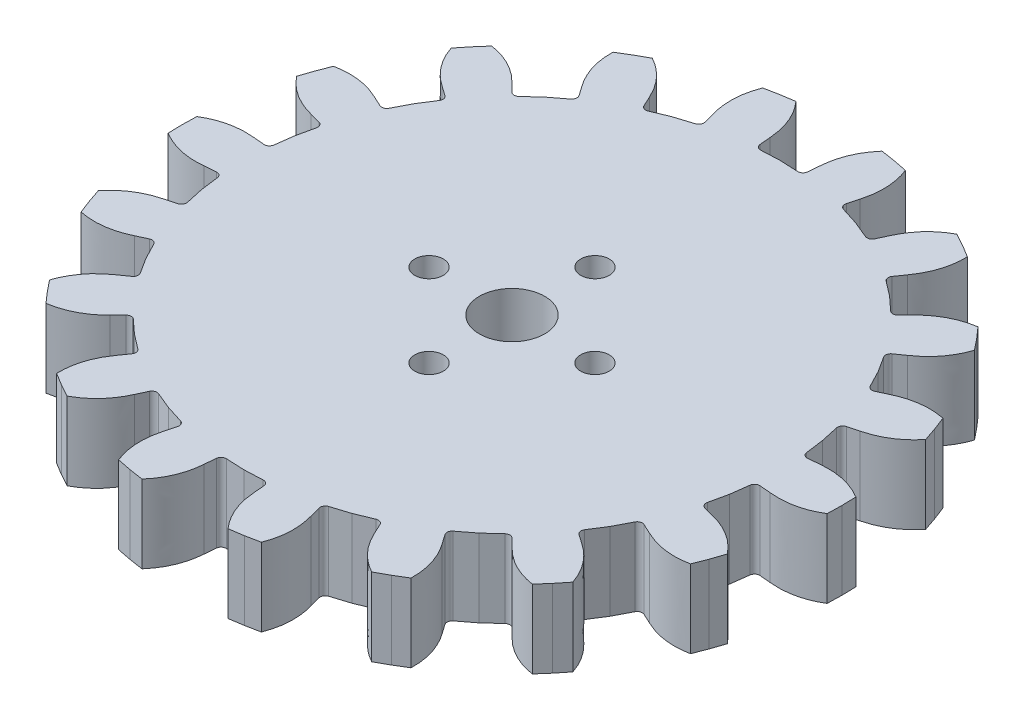
SolidWorks part; units mm, degrees
ref_plane "Front Plane" through (0, 0, 0) normal (0, 0, 1) x (1, 0, 0)
ref_plane "Top Plane" through (0, 0, 0) normal (0, 1, 0) x (1, 0, 0)
ref_plane "Right Plane" through (0, 0, 0) normal (1, 0, 0) x (0, 0, -1)
sketch "Sketch2" plane through (0, 0, 0) normal (0, 1, 0) x (1, 0, 0)
  line L0 (0, 0) -> (-45.4276, 0) construction
  line L1 (0, 0) -> (-44.5139, 1.9435) construction
  line L2 (0, 0) -> (-43.3229, 3.7903) construction
  line L3 (0, 0) -> (-25.445, 4.4866) construction
  line L4 (-25.7392, 2.2519) -> (-27.2858, 2.3872)
  line L5 (-25.7392, 2.2519) -> (-25.445, 4.4866)
  line L6 (-25.445, 4.4866) -> (0, 0)
  line L7 (-31.7697, 1.3871) -> (-31.8, 0)
  line L8 (-25.445, -4.4866) -> (0, 0)
  line L9 (-25.7392, -2.2519) -> (-25.445, -4.4866)
  line L10 (-25.7392, -2.2519) -> (-27.2858, -2.3872)
  line L11 (-31.7697, -1.3871) -> (-31.8, 0)
  circle A0 centre (0, 0) radius 25.8375 construction
  circle A1 centre (0, 0) radius 27.39 construction
  circle A2 centre (0, 0) radius 31.8 construction
  spline S0 degree 2 poles (-27.2858, 2.3872) (-29.7333, 2.6318) (-31.7697, 1.3871) knots 0 0 0 1 1 1
  spline S1 degree 2 poles (-27.2858, -2.3872) (-29.7333, -2.6318) (-31.7697, -1.3871) knots 0 0 0 1 1 1
  dimension "D1" = 63.6
  dimension "D2" = 54.78
  dimension "D3" = 51.675
  dimension "D4" = 2.5
  dimension "D5" = 10
  dimension "D6" = 5
extrude "Boss-Extrude1" add sketch "Sketch2" along normal blind 7.5
fillet "Fillet1" radius 0.5 2 edges at (-25.7392, 3.75, -2.2519) (-25.7392, 3.75, 2.2519)
pattern_circular "CirPattern1" count 18 over 360 about axis through (0, 7.5, 0) along (0, -1, 0) of "Boss-Extrude1", "Fillet1"
sketch "Sketch3" plane through (0, 7.5, 0) normal (0, 1, 0) x (1, 0, 0)
  line L0 (0, 0) -> (-15.2674, 0) construction
  circle A0 centre (0, 0) radius 3.15
  circle A1 centre (-8, 0) radius 1.375
  circle A2 centre (0, 8) radius 1.375
  circle A3 centre (8, 0) radius 1.375
  circle A4 centre (0, -8) radius 1.375
  point P15 (0, 0)
  dimension "D1" = 6.3
  dimension "D3" = 2.75
  dimension "D2" = 8
  dimension "D4" = 4
extrude "Cut-Extrude1" cut sketch "Sketch3" against normal through all
